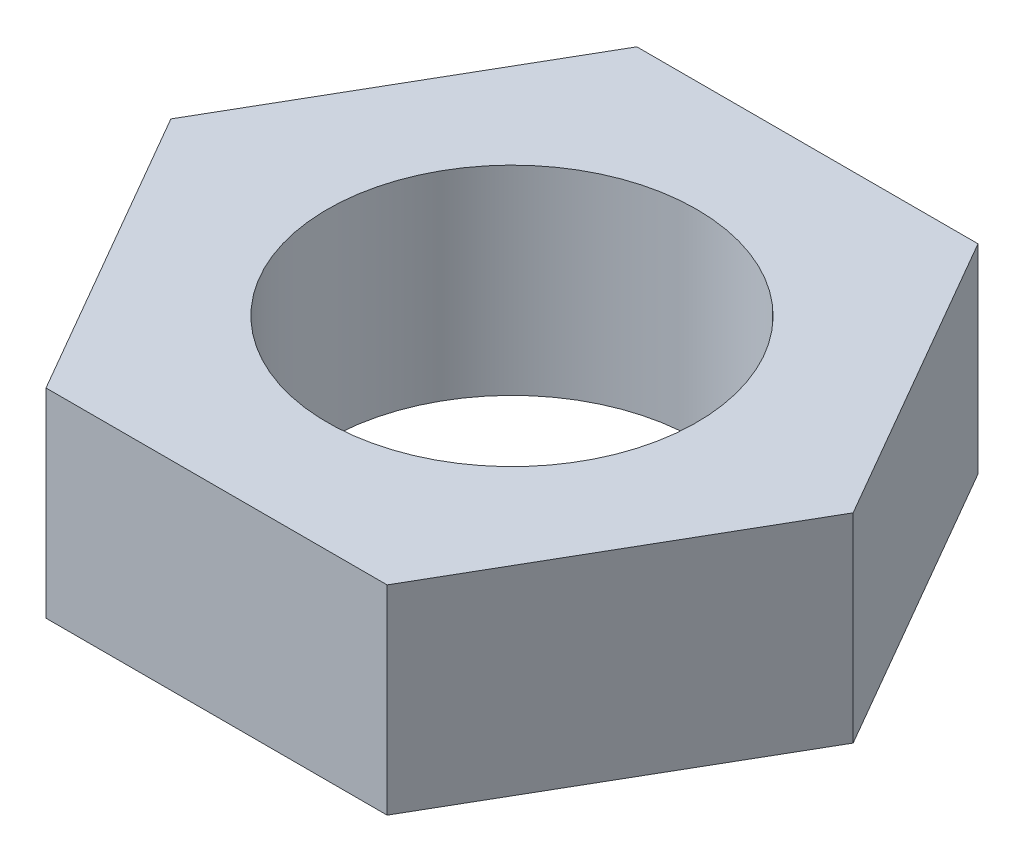
SolidWorks part; units mm, degrees
ref_plane "Front Plane" through (0, 0, 0) normal (0, 0, 1) x (1, 0, 0)
ref_plane "Top Plane" through (0, 0, 0) normal (0, 1, 0) x (1, 0, 0)
ref_plane "Right Plane" through (0, 0, 0) normal (1, 0, 0) x (0, 0, -1)
sketch "Sketch2" plane through (0, 0, 0) normal (0, 1, 0) x (1, 0, 0)
  line L1 (2.3094, 4) -> (-2.3094, 4)
  line L2 (-2.3094, 4) -> (-4.6188, 0)
  line L3 (-4.6188, 0) -> (-2.3094, -4)
  line L4 (-2.3094, -4) -> (2.3094, -4)
  line L5 (2.3094, -4) -> (4.6188, 0)
  line L6 (4.6188, 0) -> (2.3094, 4)
  circle A0 centre (0, 0) radius 4 construction
  circle A1 centre (0, 0) radius 2.5
  dimension "D2" = 5
  dimension "D1" = 8
extrude "Boss-Extrude1" add sketch "Sketch2" along normal mid plane 2.7
